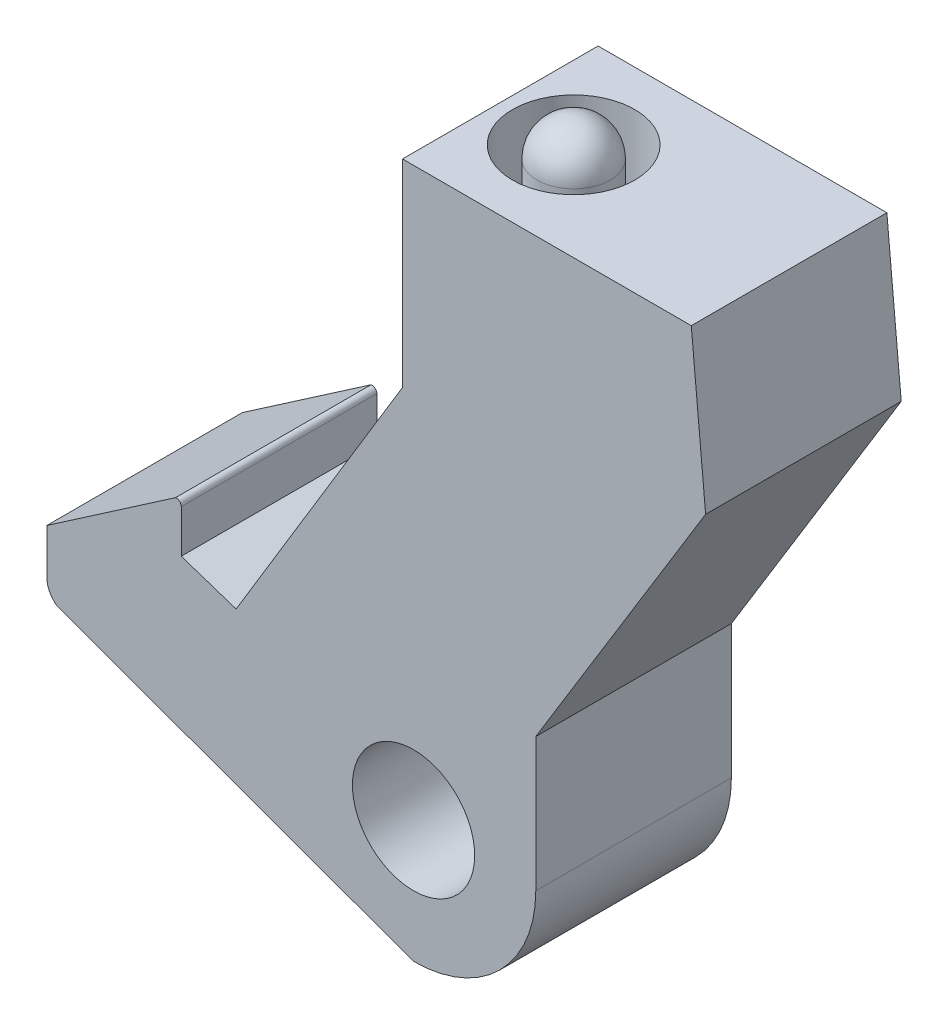
SolidWorks part; units mm, degrees
ref_plane "정면" through (0, 0, 0) normal (0, 0, 1) x (1, 0, 0)
ref_plane "윗면" through (0, 0, 0) normal (0, 1, 0) x (1, 0, 0)
ref_plane "우측면" through (0, 0, 0) normal (1, 0, 0) x (0, 0, -1)
sketch "스케치1" plane through (0, 0, 0) normal (0, 0, 1) x (1, 0, 0)
  line L0 (-0.4511, 21.8755) -> (-0.4511, 23.1959)
  line L1 (-15, 1.1119) -> (-15, 2.938)
  line L2 (11.9458, 16.8074) -> (11.359, 23.1959)
  line L3 (-9.5, 6.359) -> (-9.5, 4.5986)
  line L5 (11.359, 23.1959) -> (-0.4511, 23.1959)
  line L6 (10.1123, 13.8134) -> (11.9458, 16.8074)
  line L7 (10.1123, 13.8134) -> (5, 5.4649)
  line L8 (-14.5829, 0.2994) -> (0, -5)
  line L9 (5, 0) -> (5, 3.8348)
  line L10 (-6.5, 3.5986) -> (-0.8913, 3.5986) construction
  line L11 (-7.2581, 3.8513) -> (-9.5, 4.5986)
  line L14 (-9.7358, 6.5557) -> (-15, 2.938)
  line L15 (5, 5.4649) -> (5, 3.8348)
  line L21 (-7.2581, 3.8513) -> (-0.4511, 15.1015)
  line L22 (-0.4511, 15.1015) -> (-0.4511, 21.8755)
  circle A0 centre (0, 0) radius 2.5
  arc A1 (0, -5) -> (5, 0) centre (0, 0) ccw
  arc A3 (-9.7358, 6.5557) -> (-9.5, 6.359) centre (-9.7, 6.359) cw
  arc A5 (-14.5829, 0.2994) -> (-15, 1.1119) centre (-14, 1.1119) cw
  point P18 (-9.5, 6.5986)
  point P20 (-7.1958, -5)
  point P24 (-15, 0.5986)
  point P27 (-15, 6.5986)
  dimension "D1" = 5
  dimension "D2" = 10
  dimension "D6" = 0.2
  dimension "D3" = 6
  dimension "D4" = 9.6047
  dimension "D7" = 5.5
extrude "보스-돌출1" add sketch "스케치1" along normal blind 8
sketch "스케치5" plane through (-1.605, -4.4167, 0) normal (-0.3415, -0.9399, 0) x (0.9399, -0.3415, 0)
  line L0 (-13.8082, 8) -> (1.7077, 0) construction
  line L1 (-6.0503, 4) -> (-13.8082, 4) construction
  line L2 (-13.8082, 8) -> (-13.8082, 0) construction
  circle A0 centre (-9.9292, 4) radius 3
  dimension "D1" = 6
extrude "컷-돌출2" cut sketch "스케치5" against normal blind 3
sketch "스케치7" plane through (-0.5804, -1.5971, 0) normal (-0.3415, -0.9399, 0) x (0.9399, -0.3415, 0)
  circle A0 centre (-9.9292, 4) radius 2
extrude "보스-돌출3" add sketch "스케치7" along normal blind 3
fillet "필렛5" radius 2 1 edges at (-9.0574, -1.7085, 4)
sketch "스케치8" plane through (0, 23.1959, 0) normal (0, 1, 0) x (1, 0, 0)
  line L0 (-0.4511, -8) -> (-0.4511, 0) construction
  circle A0 centre (2.5489, -4) radius 2.5
  point P2 (-0.4511, -4)
  dimension "D2" = 5
  dimension "D1" = 3
extrude "컷-돌출3" cut sketch "스케치8" against normal blind 3
sketch "스케치9" plane through (0, 20.1959, 0) normal (0, 1, 0) x (1, 0, 0)
  circle A0 centre (2.5489, -4) radius 1.5
  dimension "D1" = 3
extrude "보스-돌출4" add sketch "스케치9" along normal blind 4
fillet "필렛6" radius 1.5 1 edges at (2.5489, 24.1959, 5.5)
